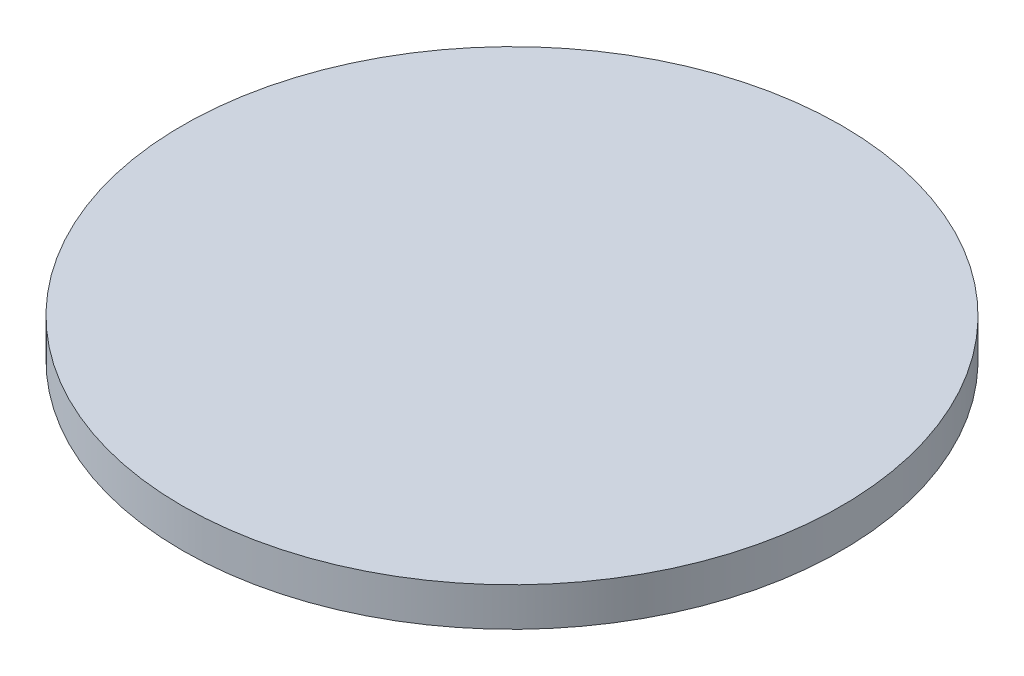
SolidWorks part; units mm, degrees
ref_plane "Front Plane" through (0, 0, 0) normal (0, 0, 1) x (1, 0, 0)
ref_plane "Top Plane" through (0, 0, 0) normal (0, 1, 0) x (1, 0, 0)
ref_plane "Right Plane" through (0, 0, 0) normal (1, 0, 0) x (0, 0, -1)
sketch "Sketch1" plane through (0, 0, 0) normal (0, 1, 0) x (1, 0, 0)
  circle A0 centre (0, 0) radius 8.54
  dimension "D1" = 17.08
extrude "Boss-Extrude1" add sketch "Sketch1" along normal blind 1
